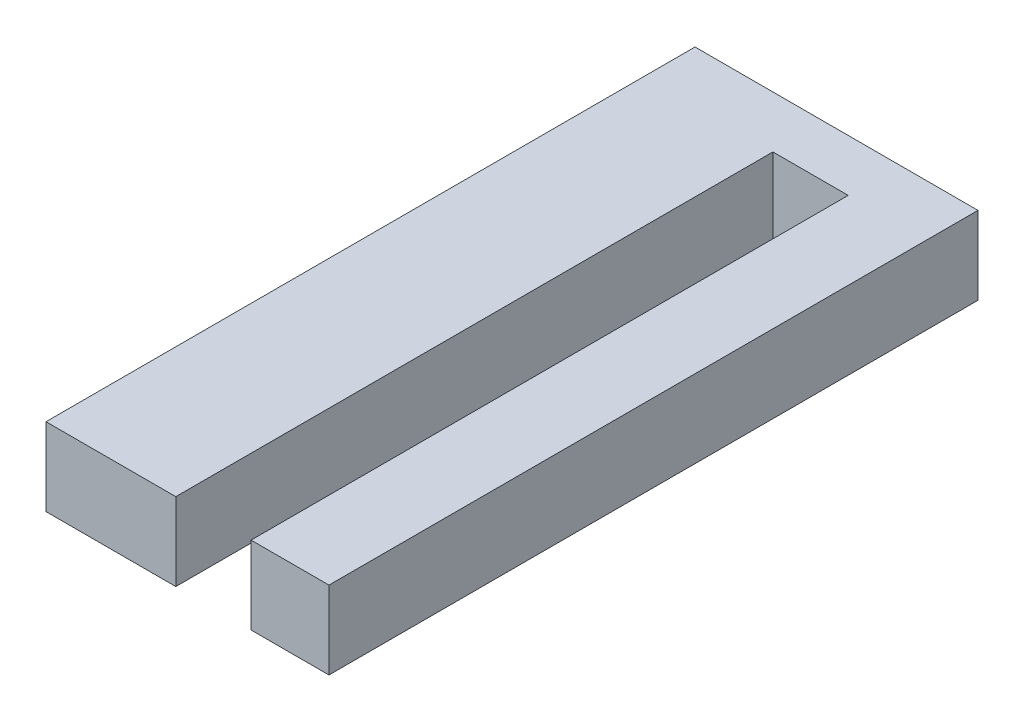
SolidWorks part; units mm, degrees
ref_plane "前视基准面" through (0, 0, 0) normal (0, 0, 1) x (1, 0, 0)
ref_plane "上视基准面" through (0, 0, 0) normal (0, 1, 0) x (1, 0, 0)
ref_plane "右视基准面" through (0, 0, 0) normal (1, 0, 0) x (0, 0, -1)
other "Configuration Table"
sketch "草图1" plane through (0, 0, 0) normal (0, 1, 0) x (1, 0, 0)
  line L0 (0, 0) -> (0, 25)
  line L1 (0, 25) -> (10.9, 25)
  line L2 (10.9, 25) -> (10.9, 0)
  line L3 (10.9, 0) -> (7.9, 0)
  line L4 (7.9, 0) -> (7.9, 23)
  line L5 (7.9, 23) -> (5, 23)
  line L6 (5, 23) -> (5, 0)
  line L7 (5, 0) -> (0, 0)
  dimension "D1" = 2.9
  dimension "D2" = 5
  dimension "D3" = 3
  dimension "D4" = 2
  dimension "D5" = 25
extrude "凸台-拉伸1" add sketch "草图1" along normal blind 3
